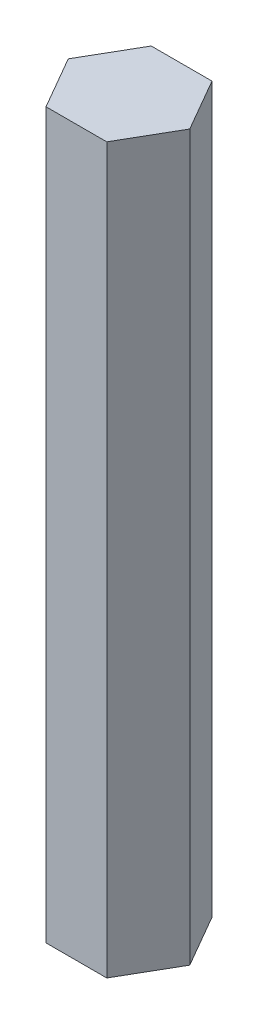
SolidWorks part; units mm, degrees
ref_plane "Front Plane" through (0, 0, 0) normal (0, 0, 1) x (1, 0, 0)
ref_plane "Top Plane" through (0, 0, 0) normal (0, 1, 0) x (1, 0, 0)
ref_plane "Right Plane" through (0, 0, 0) normal (1, 0, 0) x (0, 0, -1)
sketch "Sketch1" plane through (0, 0, 0) normal (0, 1, 0) x (1, 0, 0)
  line L1 (2.0975, 3.633) -> (-2.0975, 3.633)
  line L2 (-2.0975, 3.633) -> (-4.195, 0)
  line L3 (-4.195, 0) -> (-2.0975, -3.633)
  line L4 (-2.0975, -3.633) -> (2.0975, -3.633)
  line L5 (2.0975, -3.633) -> (4.195, 0)
  line L6 (4.195, 0) -> (2.0975, 3.633)
  circle A0 centre (0, 0) radius 3.633 construction
  dimension "D1" = 8.39
extrude "Boss-Extrude1" add sketch "Sketch1" against normal blind 50
